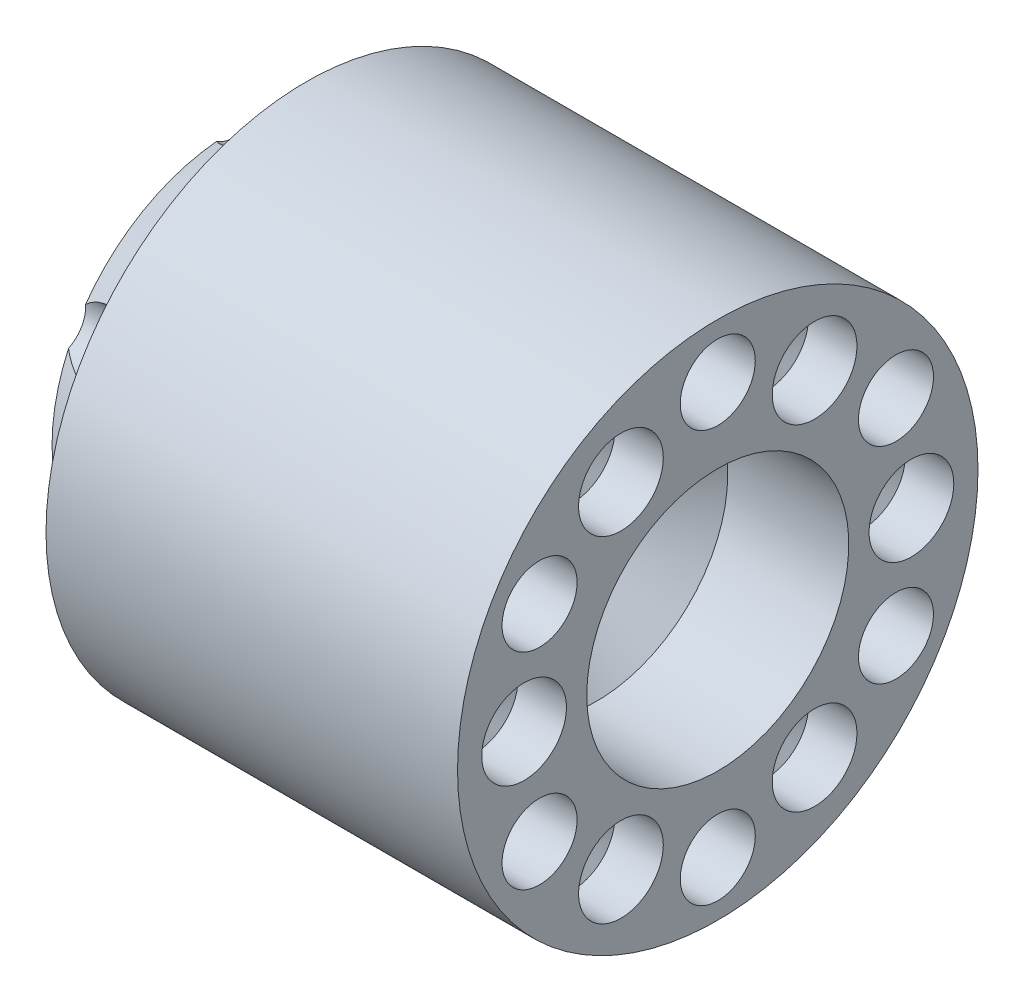
SolidWorks part; units mm, degrees
material "2018 Alloy"
ref_plane "Front Plane" through (0, 0, 0) normal (0, 0, 1) x (1, 0, 0)
ref_plane "Top Plane" through (0, 0, 0) normal (0, 1, 0) x (1, 0, 0)
ref_plane "Right Plane" through (0, 0, 0) normal (1, 0, 0) x (0, 0, -1)
sketch "Sketch1" plane through (0, 0, 0) normal (0, 0, 1) x (1, 0, 0)
  line L2 (6, 18.5) -> (0, 15)
  line L4 (0, 9.0675) -> (0, 0) construction
  line L5 (40, 0) -> (40, 10.825) construction
  line L7 (0, 0) -> (40, 0) construction
  line L13 (40, 10.825) -> (30, 10.825)
  line L14 (30, 10.825) -> (25.675, 6.5)
  line L15 (25.675, 6.5) -> (0, 9.0675)
  line L16 (6, 18.5) -> (6, 21.5)
  line L17 (6, 21.5) -> (40, 21.5)
  line L18 (0, 15) -> (0, 9.0675)
  line L26 (40, 21.5) -> (40, 10.825)
  line L27 (25.675, 6.5) -> (15.675, 6.5) construction
  line L28 (15.675, 6.5) -> (15.675, 7.5) construction
  dimension "D4" = 40
  dimension "D5" = 34
  dimension "D6" = 10
  dimension "D8" = 21.65
  dimension "D9" = 45
  dimension "D10" = 13
  dimension "D13" = 6
  dimension "D14" = 37
  dimension "D15" = 30
  dimension "D16" = 43
  dimension "D17" = 59.744
  dimension "D19" = 25.675
  dimension "D20" = 10
  dimension "D27" = 1
  dimension "D28" = 5.711
  dimension "D29" = 18.135
  dimension "D31" = 4.325
revolve "Revolve1" add sketch "Sketch1" angle 360 about L7
sketch "Sketch11" plane through (40, 0, 0) normal (1, 0, 0) x (0, 0, -1)
  line L0 (0, 0) -> (0, -17) construction
  circle A0 centre (0, 0) radius 17 construction
  circle A1 centre (0, -17) radius 3.1
  circle A2 centre (-14.7224, -8.5) radius 3.1
  circle A3 centre (-14.7224, 8.5) radius 3.1
  circle A4 centre (0, 17) radius 3.1
  circle A5 centre (14.7224, 8.5) radius 3.1
  circle A6 centre (14.7224, -8.5) radius 3.1
  dimension "D1" = 34
  dimension "D2" = 6.2
extrude "Extrude1" cut sketch "Sketch11" against normal blind 12
sketch "Sketch12" plane through (28, 0, 0) normal (1, 0, 0) x (0, 0, -1)
  circle A0 centre (0, -17) radius 3
  circle A1 centre (-14.7224, -8.5) radius 3
  circle A2 centre (-14.7224, 8.5) radius 3
  circle A3 centre (0, 17) radius 3
  circle A4 centre (14.7224, 8.5) radius 3
  circle A5 centre (14.7224, -8.5) radius 3
  dimension "D1" = 6
hole_wizard "M6 Tapped Hole1" positions "3DSketch1" profile "Sketch13" tap size "M6" standard "DIN"
sketch3d "3DSketch1"
  point P0 (28, -17, 0)
  point P3 (28, -8.5, 14.7224)
  point P6 (28, 8.5, 14.7224)
  point P9 (28, 17, 0)
  point P12 (28, 8.5, -14.7224)
  point P15 (28, -8.5, -14.7224)
sketch "Sketch13" plane through (28, -17, 0) normal (0, 1, 0) x (0, 0, -1)
  line L0 (0, 0) -> (0, 36.5022)
  line L1 (0, 36.5022) -> (2.5, 35)
  line L2 (2.5, 35) -> (2.5, 0)
  line L5 (2.5, 0) -> (0, 0)
  line L10 (0, 36.5022) -> (-2.5, 35) construction
  line L11 (0, -6.35) -> (0, 107.95) construction
  dimension "Tap Drill Dia." = 5
  dimension "Tap Drill Depth" = 35
  dimension "Drill Angle" = 118
cosmetic thread "Hole Thread3"
cosmetic thread "Hole Thread4"
cosmetic thread "Hole Thread5"
cosmetic thread "Hole Thread6"
cosmetic thread "Hole Thread7"
cosmetic thread "Hole Thread8"
sketch "Sketch14" plane through (40, 0, 0) normal (1, 0, 0) x (0, 0, -1)
  line L0 (0, -16) -> (0, 0) construction
  line L1 (0, 0) -> (8, -13.8564) construction
  circle A0 centre (0, 0) radius 16 construction
  circle A1 centre (8, -13.8564) radius 3.5
  circle A2 centre (-8, -13.8564) radius 3.5
  circle A3 centre (-16, 0) radius 3.5
  circle A4 centre (-8, 13.8564) radius 3.5
  circle A5 centre (8, 13.8564) radius 3.5
  circle A6 centre (16, 0) radius 3.5
  dimension "D1" = 32
  dimension "D3" = 7
  dimension "D2" = 30
hole_wizard "Ø7.0 (7) Diameter Hole1" positions "3DSketch2" profile "Sketch15" hole size "Ø7.0" standard "DIN"
sketch3d "3DSketch2"
  point P0 (40, -13.8564, -8)
  point P3 (40, -13.8564, 8)
  point P6 (40, 0, 16)
  point P9 (40, 13.8564, 8)
  point P12 (40, 13.8564, -8)
  point P15 (40, 0, -16)
sketch "Sketch15" plane through (40, -13.8564, -8) normal (0, 1, 0) x (0, 0, -1)
  line L0 (0, 0) -> (0, 6.103)
  line L1 (0, 6.103) -> (3.5, 4)
  line L2 (3.5, 4) -> (3.5, 0)
  line L5 (3.5, 0) -> (0, 0)
  line L10 (0, 6.103) -> (-3.5, 4) construction
  line L11 (0, -6.35) -> (0, 107.95) construction
  dimension "Hole Dia." = 7
  dimension "Hole Depth" = 4
  dimension "Drill Angle" = 118
sketch "Sketch17" plane through (0, 0, 0) normal (0, 0, 1) x (1, 0, 0)
  line L0 (0, 0) -> (0, 33.2506)
sketch "Sketch18" plane through (0, 0, 0) normal (0, 0, 1) x (1, 0, 0)
  line L0 (28.5706, 5.306) -> (-3.0747, 8.4705)
  line L1 (-3.0747, 8.4705) -> (-2.7762, 11.4556)
  line L2 (-2.7762, 11.4556) -> (28.8691, 8.2911)
  line L3 (28.8691, 8.2911) -> (28.5706, 5.306)
  line L4 (25.675, 6.5) -> (0, 9.0675) construction
  dimension "D1" = 2.1
  dimension "D2" = 3
  dimension "D3" = 3
  dimension "D4" = 3
extrude "Extrude3" cut sketch "Sketch18" against normal mid plane 7
